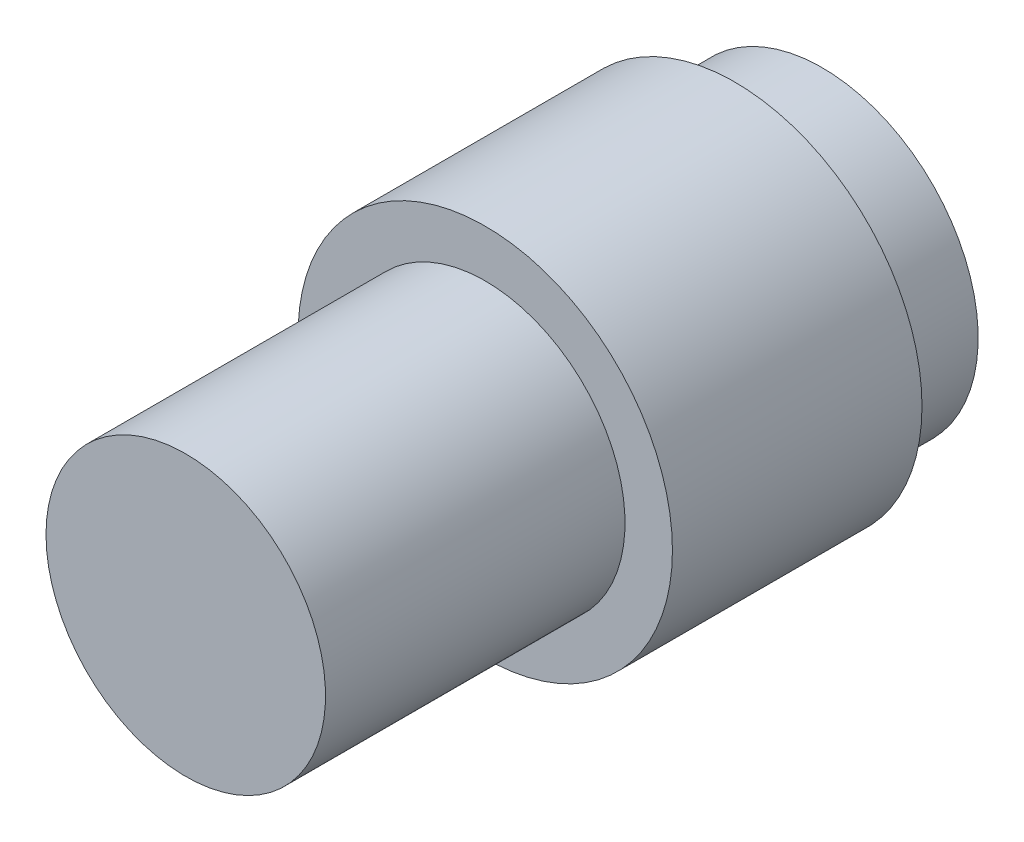
SolidWorks part; units mm, degrees
ref_plane "Front Plane" through (0, 0, 0) normal (0, 0, 1) x (1, 0, 0)
ref_plane "Top Plane" through (0, 0, 0) normal (0, 1, 0) x (1, 0, 0)
ref_plane "Right Plane" through (0, 0, 0) normal (1, 0, 0) x (0, 0, -1)
sketch "Sketch1" plane through (0, 0, 0) normal (0, 0, 1) x (1, 0, 0)
  circle A0 centre (0, 0) radius 1.905
  dimension "D1" = 3.81
extrude "Boss-Extrude1" add sketch "Sketch1" along normal blind 2.54
sketch "Sketch2" plane through (0, 0, 2.54) normal (0, 0, 1) x (1, 0, 0)
  circle A0 centre (0, 0) radius 1.4224
  dimension "D1" = 2.8448
extrude "Boss-Extrude2" add sketch "Sketch2" along normal blind 3.048
sketch "Sketch3" plane through (0, 0, 0) normal (0, 0, -1) x (-1, 0, 0)
  circle A0 centre (0, 0) radius 1.5875
  dimension "D1" = 3.175
extrude "Boss-Extrude3" add sketch "Sketch3" along normal blind 0.889
